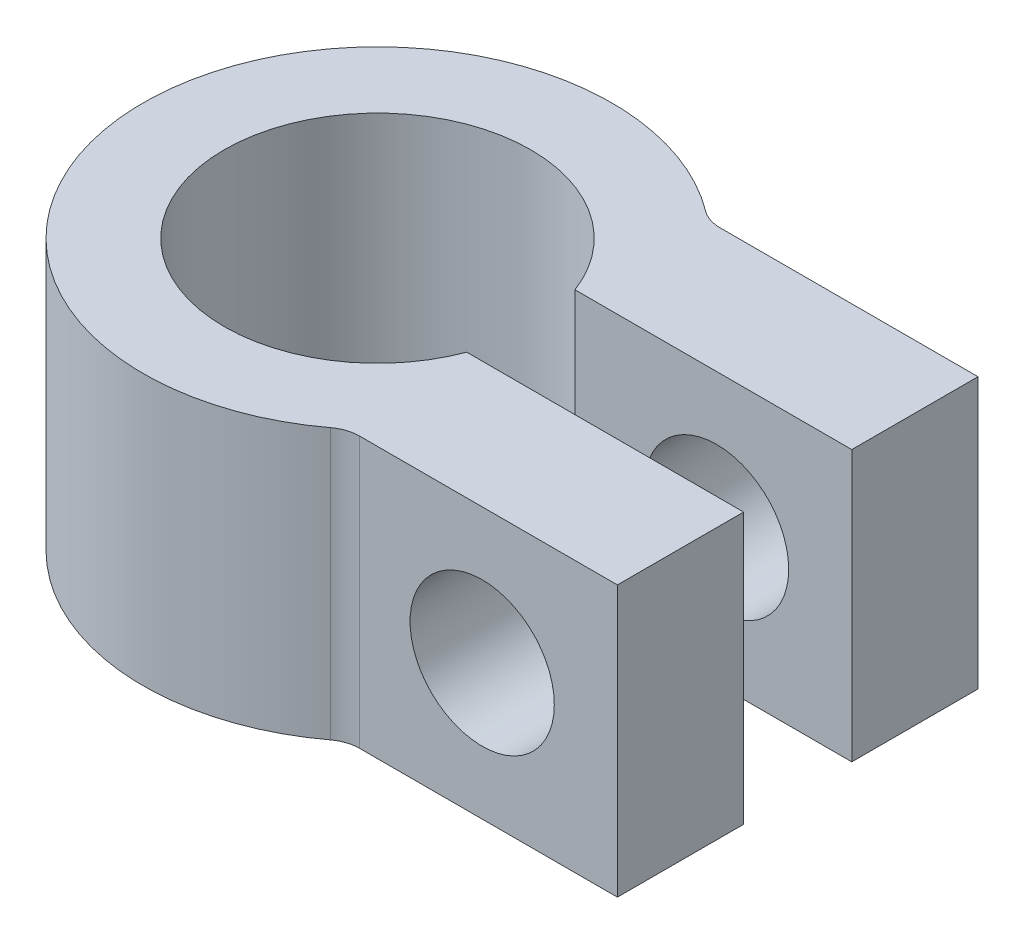
SolidWorks part; units mm, degrees
material "Manual Density from Real Component Anello di fissaggio 16"
ref_plane "Piano frontale" through (0, 0, 0) normal (0, 0, 1) x (1, 0, 0)
ref_plane "Piano superiore" through (0, 0, 0) normal (0, 1, 0) x (1, 0, 0)
ref_plane "Piano destro" through (0, 0, 0) normal (1, 0, 0) x (0, 0, -1)
sketch "Schizzo3" plane through (0, 0, 0) normal (0, 1, 0) x (1, 0, 0)
  circle A0 centre (0, 0) radius 8.5
  circle A1 centre (0, 0) radius 13
  dimension "D1" = 26
  dimension "D2" = 17
extrude "Anello" add sketch "Schizzo3" along normal blind 15
sketch "Schizzo4" plane through (0, 0, 0) normal (0, 1, 0) x (1, 0, 0)
  line L0 (23.3066, 3) -> (12.6491, 3)
  line L3 (8.3066, 10) -> (23.3066, 10)
  line L4 (23.3066, 3) -> (23.3066, 10)
  circle A1 centre (0, 0) radius 13 construction
  arc A2 (8.3066, 10) -> (12.6491, 3) centre (0, 0) cw
  dimension "D1" = 7
  dimension "D2" = 15
  dimension "D3" = 3
extrude "AggancioAlto" add sketch "Schizzo4" along normal up to surface (15 mm away) up to face at (0, 15, 13)
mirror "AggancioBasso" about plane through (0, 0, 0) normal (0, 0, 1) of "AggancioAlto"
sketch "Schizzo5" plane through (0, 15, 0) normal (0, 1, 0) x (1, 0, 0)
  line L1 (0, 3) -> (23.3066, 3)
  line L2 (0, 3) -> (0, -3)
  line L3 (0, -3) -> (23.3066, -3)
  line L4 (23.3066, 3) -> (23.3066, -3)
  point P4 (0, 0)
extrude "AperturaAnello" cut sketch "Schizzo5" against normal through all
sketch "Schizzo6" plane through (0, 0, 10) normal (0, 0, 1) x (1, 0, 0)
  line L0 (23.3066, 15) -> (23.3066, 0) construction
  line L1 (23.3066, 15) -> (8.3066, 15) construction
  circle A0 centre (15.8066, 7.5) radius 4
  point P4 (23.3066, 7.5)
  point P8 (15.8066, 15)
  dimension "D1" = 8
extrude "ForoPassante" cut sketch "Schizzo6" against normal through all
fillet "RaccordoBasso" radius 2 1 edges at (8.3066, 7.5, 10)
fillet "RaccordoAlto" radius 2 1 edges at (8.3066, 7.5, -10)
